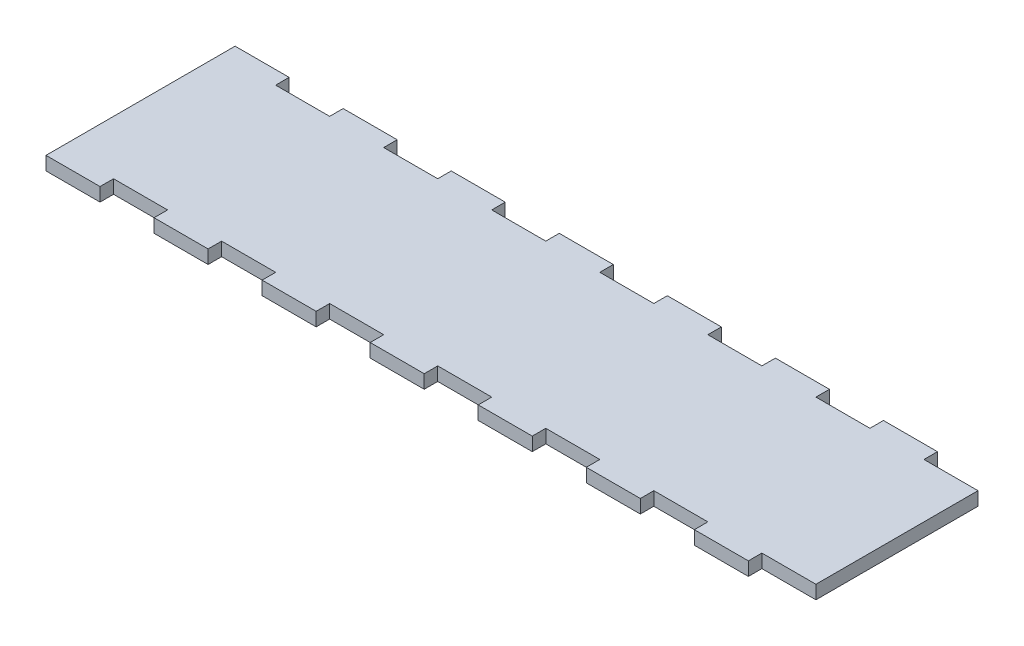
SolidWorks part; units mm, degrees
material "Acrylic (Medium-high impact)"
ref_plane "Front Plane" through (0, 0, 0) normal (0, 0, 1) x (1, 0, 0)
ref_plane "Top Plane" through (0, 0, 0) normal (0, 1, 0) x (1, 0, 0)
ref_plane "Right Plane" through (0, 0, 0) normal (1, 0, 0) x (0, 0, -1)
sketch "Sketch1" plane through (0, 0, 0) normal (0, 1, 0) x (1, 0, 0)
  line L0 (0, -22.225) -> (177.8, -22.225) construction
  line L1 (0, 0) -> (177.8, 0)
  line L2 (0, 0) -> (0, -44.45)
  line L3 (0, -44.45) -> (177.8, -44.45)
  line L4 (177.8, 0) -> (177.8, -44.45)
  line L5 (25.4, -44.45) -> (25.4, -41.275)
  line L6 (12.7, 0) -> (25.4, 0)
  line L7 (12.7, 0) -> (12.7, -3.175)
  line L8 (12.7, -3.175) -> (25.4, -3.175)
  line L9 (25.4, 0) -> (25.4, -3.175)
  line L10 (12.7, -41.275) -> (25.4, -41.275)
  line L11 (12.7, -44.45) -> (12.7, -41.275)
  line L12 (50.8, 0) -> (50.8, -3.175)
  line L13 (38.1, -3.175) -> (50.8, -3.175)
  line L14 (38.1, 0) -> (38.1, -3.175)
  line L15 (50.8, -44.45) -> (50.8, -41.275)
  line L16 (38.1, -41.275) -> (50.8, -41.275)
  line L17 (38.1, -44.45) -> (38.1, -41.275)
  line L18 (76.2, 0) -> (76.2, -3.175)
  line L19 (63.5, -3.175) -> (76.2, -3.175)
  line L20 (63.5, 0) -> (63.5, -3.175)
  line L21 (76.2, -44.45) -> (76.2, -41.275)
  line L22 (63.5, -41.275) -> (76.2, -41.275)
  line L23 (63.5, -44.45) -> (63.5, -41.275)
  line L24 (101.6, 0) -> (101.6, -3.175)
  line L25 (88.9, -3.175) -> (101.6, -3.175)
  line L26 (88.9, 0) -> (88.9, -3.175)
  line L27 (101.6, -44.45) -> (101.6, -41.275)
  line L28 (88.9, -41.275) -> (101.6, -41.275)
  line L29 (88.9, -44.45) -> (88.9, -41.275)
  line L30 (127, 0) -> (127, -3.175)
  line L31 (114.3, -3.175) -> (127, -3.175)
  line L32 (114.3, 0) -> (114.3, -3.175)
  line L33 (127, -44.45) -> (127, -41.275)
  line L34 (114.3, -41.275) -> (127, -41.275)
  line L35 (114.3, -44.45) -> (114.3, -41.275)
  line L36 (38.1, 0) -> (38.1, -3.175)
  line L37 (38.1, -3.175) -> (50.8, -3.175)
  line L38 (50.8, 0) -> (50.8, -3.175)
  line L39 (38.1, -44.45) -> (38.1, -41.275)
  line L40 (38.1, -41.275) -> (50.8, -41.275)
  line L41 (50.8, -44.45) -> (50.8, -41.275)
  line L42 (63.5, 0) -> (63.5, -3.175)
  line L43 (63.5, -3.175) -> (76.2, -3.175)
  line L44 (76.2, 0) -> (76.2, -3.175)
  line L45 (63.5, -44.45) -> (63.5, -41.275)
  line L46 (63.5, -41.275) -> (76.2, -41.275)
  line L47 (76.2, -44.45) -> (76.2, -41.275)
  line L48 (88.9, 0) -> (88.9, -3.175)
  line L49 (88.9, -3.175) -> (101.6, -3.175)
  line L50 (101.6, 0) -> (101.6, -3.175)
  line L51 (88.9, -44.45) -> (88.9, -41.275)
  line L52 (88.9, -41.275) -> (101.6, -41.275)
  line L53 (101.6, -44.45) -> (101.6, -41.275)
  line L54 (114.3, 0) -> (114.3, -3.175)
  line L55 (114.3, -3.175) -> (127, -3.175)
  line L56 (127, 0) -> (127, -3.175)
  line L57 (114.3, -44.45) -> (114.3, -41.275)
  line L58 (114.3, -41.275) -> (127, -41.275)
  line L59 (127, -44.45) -> (127, -41.275)
  line L60 (139.7, 0) -> (139.7, -3.175)
  line L61 (139.7, -3.175) -> (152.4, -3.175)
  line L62 (152.4, 0) -> (152.4, -3.175)
  line L63 (139.7, -44.45) -> (139.7, -41.275)
  line L64 (139.7, -41.275) -> (152.4, -41.275)
  line L65 (152.4, -44.45) -> (152.4, -41.275)
  line L66 (165.1, 0) -> (165.1, -3.175)
  line L67 (165.1, -3.175) -> (177.8, -3.175)
  line L68 (177.8, 0) -> (177.8, -3.175)
  line L69 (165.1, -44.45) -> (165.1, -41.275)
  line L70 (165.1, -41.275) -> (177.8, -41.275)
  line L71 (177.8, -44.45) -> (177.8, -41.275)
  dimension "D1" = 177.8
  dimension "D2" = 44.45
  dimension "D3" = 12.7
  dimension "D4" = 3.175
  dimension "D5" = 12.7
  dimension "D7" = 12.7
  dimension "D6" = 5
  dimension "D8" = 7
extrude "Boss-Extrude1" add sketch "Sketch1" along normal blind 3.175 contours L0 L2 L3 L11 L10 L5 L17 L16 L15 L23 L22 L21 L29 L28 L27 L35 L34 L33 L4 | L2 L0 L4 L1 L30 L31 L32 L24 L25 L26 L18 L19 L20 L12 L13 L14 L9 L8 L7
